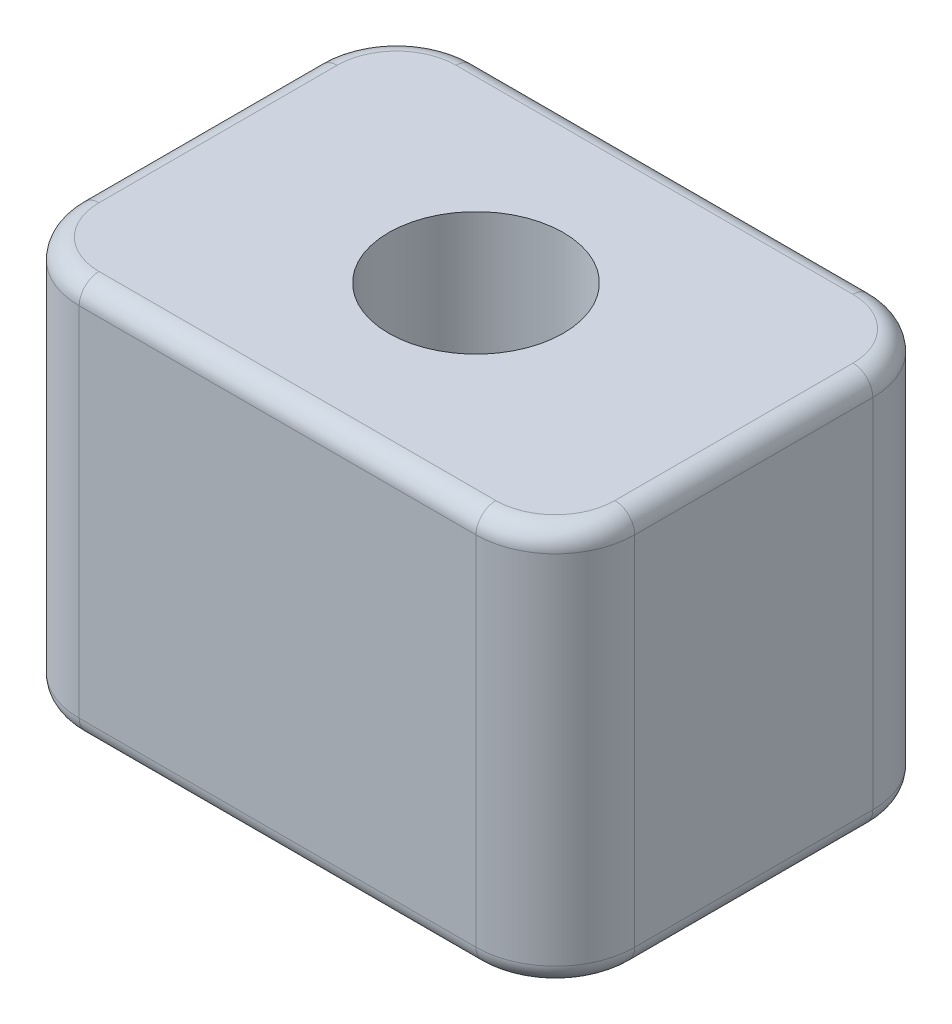
SolidWorks part; units mm, degrees
ref_plane "前视基准面" through (0, 0, 0) normal (0, 0, 1) x (1, 0, 0)
ref_plane "上视基准面" through (0, 0, 0) normal (0, 1, 0) x (1, 0, 0)
ref_plane "右视基准面" through (0, 0, 0) normal (1, 0, 0) x (0, 0, -1)
sketch "草图1" plane through (0, 0, 0) normal (0, 1, 0) x (1, 0, 0)
  line L1 (-3.5, -2.5) -> (3.5, -2.5)
  line L2 (-3.5, -2.5) -> (-3.5, 2.5)
  line L3 (-3.5, 2.5) -> (3.5, 2.5)
  line L4 (3.5, -2.5) -> (3.5, 2.5)
  line L5 (-3.5, -2.5) -> (3.5, 2.5) construction
  line L6 (-3.5, 2.5) -> (3.5, -2.5) construction
  circle A0 centre (0, 0) radius 1.1
  point P0 (0, 0)
  dimension "D3" = 2.2
  dimension "D1" = 7
  dimension "D2" = 5
extrude "凸台-拉伸1" add sketch "草图1" along normal blind 5
fillet "圆角2" radius 1 4 edges at (3.5, 2.5, -2.5) (3.5, 2.5, 2.5) (-3.5, 2.5, 2.5) (-3.5, 2.5, -2.5)
fillet "圆角1" radius 0.25 16 edges at (3.5, 0, 0) (0, 0, 2.5) (0, 0, -2.5) (-3.5, 0, 0) (-3.2071, 0, -2.2071) (3.2071, 0, -2.2071) (3.2071, 0, 2.2071) (-3.2071, 0, 2.2071) (-3.2071, 5, 2.2071) (-3.5, 5, 0) (-3.2071, 5, -2.2071) (0, 5, -2.5) (3.2071, 5, -2.2071) (3.5, 5, 0) (3.2071, 5, 2.2071) (0, 5, 2.5)
